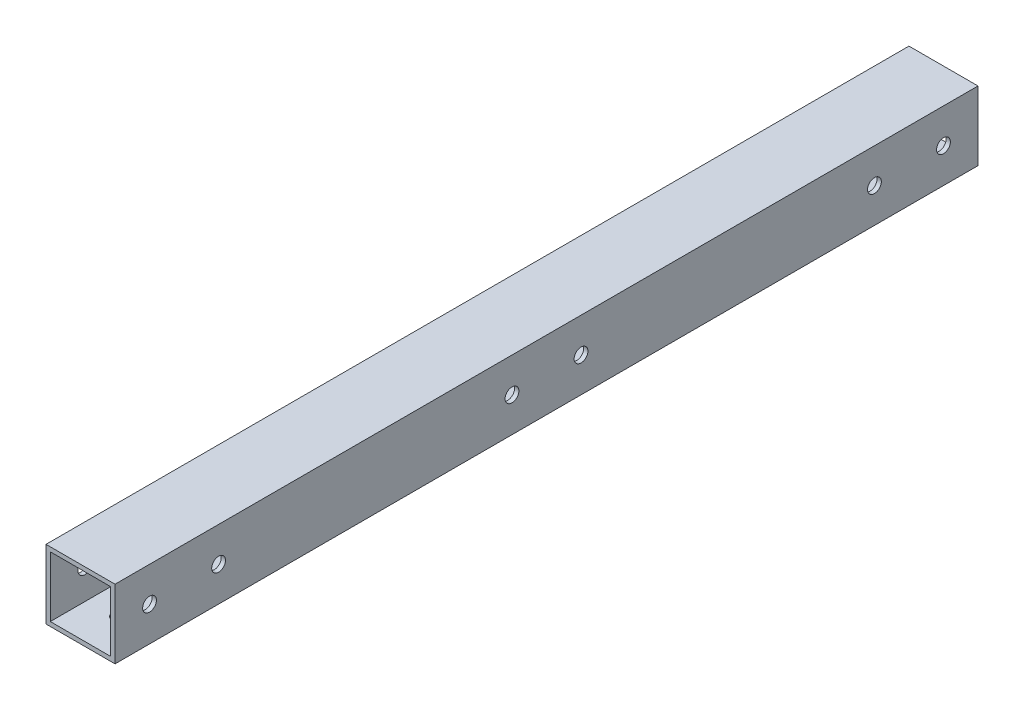
SolidWorks part; units mm, degrees
ref_plane "Front Plane" through (0, 0, 0) normal (0, 0, 1) x (1, 0, 0)
ref_plane "Top Plane" through (0, 0, 0) normal (0, 1, 0) x (1, 0, 0)
ref_plane "Right Plane" through (0, 0, 0) normal (1, 0, 0) x (0, 0, -1)
sketch "Sketch1" plane through (0, 0, 0) normal (0, 0, 1) x (1, 0, 0)
  line L1 (0, 0) -> (25.4, 0)
  line L2 (0, 0) -> (0, 25.4)
  line L3 (0, 25.4) -> (25.4, 25.4)
  line L4 (25.4, 0) -> (25.4, 25.4)
  line L5 (1.5875, 1.5875) -> (23.8125, 1.5875)
  line L6 (1.5875, 1.5875) -> (1.5875, 23.8125)
  line L7 (1.5875, 23.8125) -> (23.8125, 23.8125)
  line L8 (23.8125, 1.5875) -> (23.8125, 23.8125)
  dimension "D1" = 25.4
  dimension "D2" = 1.5875
  dimension "D3" = 1.5875
  dimension "D4" = 1.5875
  dimension "D5" = 1.5875
extrude "Boss-Extrude1" add sketch "Sketch1" along normal blind 317.5
sketch "Sketch4" plane through (25.4, 0, 0) normal (1, 0, 0) x (0, 0, -1)
  line L0 (-317.5, 25.4) -> (0, 25.4) construction
  line L1 (-317.5, 0) -> (-317.5, 25.4) construction
  line L2 (-158.75, 25.4) -> (-158.75, 0) construction
  line L3 (-317.5, 0) -> (0, 0) construction
  circle A0 centre (-304.8, 12.7) radius 2.54
  circle A2 centre (-279.4, 12.7) radius 2.54
  circle A12 centre (-38.1, 12.7) radius 2.54
  circle A13 centre (-12.7, 12.7) radius 2.54
  circle A14 centre (-171.45, 12.7) radius 2.54
  circle A15 centre (-146.05, 12.7) radius 2.54
  dimension "D1" = 5.08
  dimension "D2" = 12.7
  dimension "D3" = 12.7
  dimension "D4" = 2
  dimension "D5" = 12.7
extrude "Cut-Extrude3" cut sketch "Sketch4" against normal through all
sketch "Sketch5" plane through (0, 0, 0) normal (0, -1, 0) x (1, 0, 0)
  line L0 (12.7, 317.5) -> (12.7, 0) construction
  line L1 (0, 317.5) -> (25.4, 317.5) construction
  line L2 (0, 0) -> (25.4, 0) construction
  line L4 (25.4, 317.5) -> (25.4, 0) construction
  line L5 (25.4, 158.75) -> (0, 158.75) construction
  circle A0 centre (12.7, 303.2125) radius 2.54
  circle A1 centre (12.7, 14.2875) radius 2.54
  dimension "D1" = 5.08
  dimension "D2" = 14.2875
extrude "Cut-Extrude4" cut sketch "Sketch5" against normal up to next
